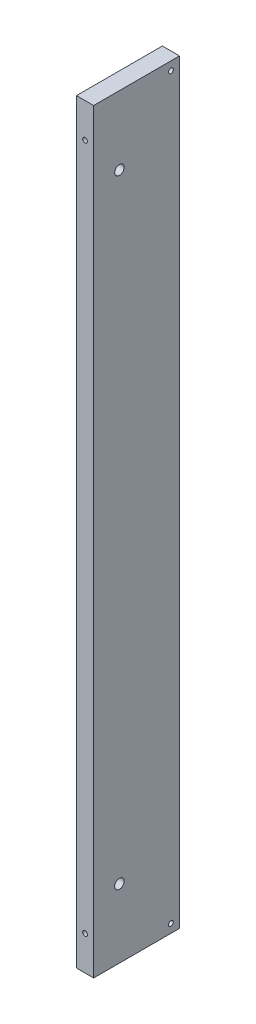
SolidWorks part; units mm, degrees
ref_plane "Front Plane" through (0, 0, 0) normal (0, 0, 1) x (1, 0, 0)
ref_plane "Top Plane" through (0, 0, 0) normal (0, 1, 0) x (1, 0, 0)
ref_plane "Right Plane" through (0, 0, 0) normal (1, 0, 0) x (0, 0, -1)
sketch "Sketch3" plane through (0, 0, 0) normal (0, 0, 1) x (1, 0, 0)
  line L1 (0, 0) -> (10, 0)
  line L2 (0, 0) -> (0, 440)
  line L3 (0, 440) -> (10, 440)
  line L4 (10, 0) -> (10, 440)
  dimension "D1" = 440
  dimension "D2" = 10
extrude "Boss-Extrude1" add sketch "Sketch3" along normal blind 50
sketch "Sketch4" plane through (0, 0, 50) normal (0, 0, 1) x (1, 0, 0)
  line L0 (10, 440) -> (0, 440) construction
  line L1 (0, 440) -> (0, 0) construction
  line L2 (0, 0) -> (10, 0) construction
  circle A0 centre (5, 420) radius 1.4
  circle A1 centre (5, 20) radius 1.4
  dimension "D1" = 2.8
  dimension "D2" = 2.8
  dimension "D3" = 20
  dimension "D4" = 5
  dimension "D5" = 20
  dimension "D6" = 5
extrude "Cut-Extrude2" cut sketch "Sketch4" against normal blind 10
sketch "Sketch5" plane through (0, 0, 0) normal (-1, 0, 0) x (0, 0, 1)
  line L0 (50, 0) -> (0, 0) construction
  line L1 (50, 440) -> (50, 0) construction
  line L2 (50, 440) -> (0, 440) construction
  circle A0 centre (35, 400) radius 2.75
  circle A1 centre (35, 40) radius 2.75
  dimension "D1" = 5.5
  dimension "D2" = 5.5
  dimension "D3" = 40
  dimension "D4" = 15
  dimension "D5" = 40
  dimension "D6" = 15
extrude "Cut-Extrude3" cut sketch "Sketch5" against normal blind 10
sketch "Sketch6" plane through (0, 0, 0) normal (-1, 0, 0) x (0, 0, 1)
  line L0 (50, 440) -> (0, 440) construction
  line L1 (0, 440) -> (0, 0) construction
  line L2 (50, 0) -> (0, 0) construction
  circle A0 centre (5, 435) radius 1.4
  circle A1 centre (5, 5) radius 1.4
  dimension "D1" = 2.8
  dimension "D2" = 2.8
  dimension "D3" = 5
  dimension "D4" = 5
  dimension "D5" = 5
  dimension "D6" = 5
extrude "Cut-Extrude4" cut sketch "Sketch6" against normal blind 10
